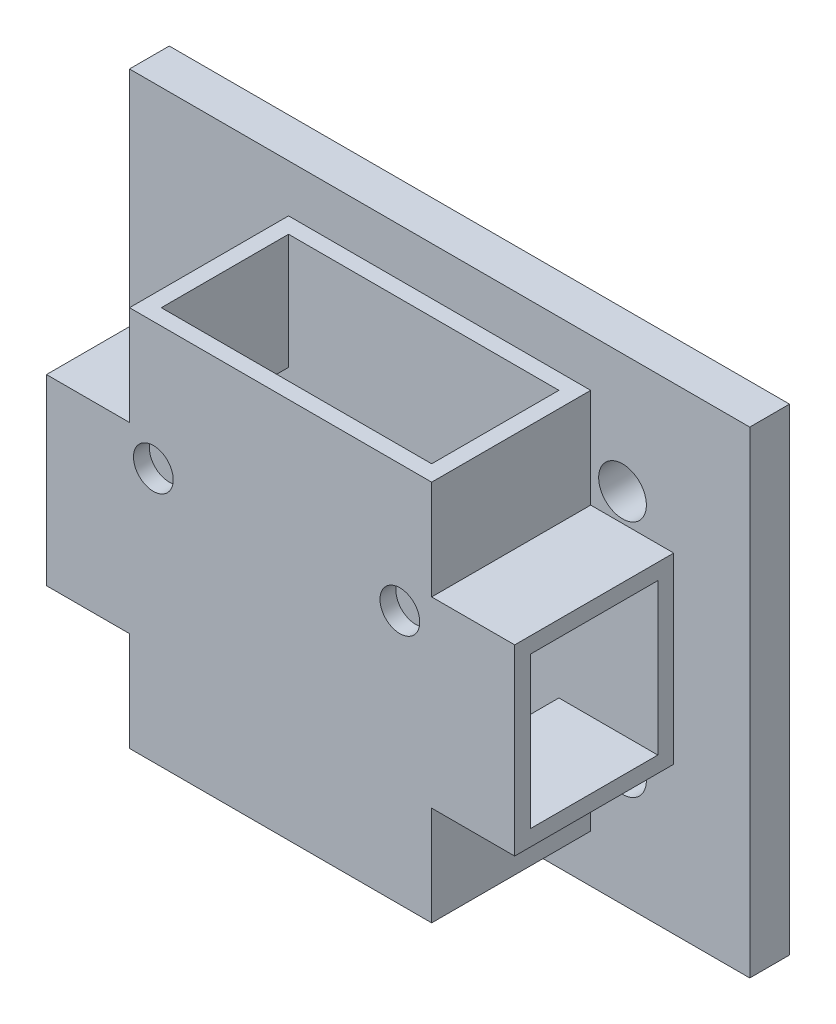
SolidWorks part; units mm, degrees
ref_plane "Front Plane" through (0, 0, 0) normal (0, 0, 1) x (1, 0, 0)
ref_plane "Top Plane" through (0, 0, 0) normal (0, 1, 0) x (1, 0, 0)
ref_plane "Right Plane" through (0, 0, 0) normal (1, 0, 0) x (0, 0, -1)
sketch "Sketch1" plane through (0, 0, 0) normal (0, 0, 1) x (1, 0, 0)
  line L1 (-39.2125, 39.1063) -> (38.7875, 39.1063)
  line L2 (-39.2125, 39.1063) -> (-39.2125, -20.8937)
  line L3 (-39.2125, -20.8937) -> (38.7875, -20.8937)
  line L4 (38.7875, 39.1063) -> (38.7875, -20.8937)
  dimension "D1" = 78
  dimension "D2" = 60
extrude "Boss-Extrude1" add sketch "Sketch1" along normal blind 5
sketch "Sketch7" plane through (0, 0, 5) normal (0, 0, 1) x (1, 0, 0)
  line L0 (-39.2125, 39.1063) -> (-39.2125, -20.8937) construction
  line L1 (-39.2125, -20.8937) -> (38.7875, -20.8937) construction
  line L2 (38.7875, -20.8937) -> (38.7875, 39.1063) construction
  circle A0 centre (-23.2125, 24.1063) radius 3
  circle A1 centre (22.7875, 24.1063) radius 3
  circle A2 centre (22.7875, -5.8937) radius 3
  circle A3 centre (-23.2125, -5.8937) radius 3
  point P0 (-23.2125, 24.1063)
  point P1 (22.7875, 24.1063)
  point P2 (22.7875, -5.8937)
  point P3 (-23.2125, -5.8937)
  dimension "D6" = 6
  dimension "D7" = 6
  dimension "D8" = 6
  dimension "D9" = 6
  dimension "D1" = 46
  dimension "D2" = 46
  dimension "D3" = 30
  dimension "D4" = 16
  dimension "D5" = 15
  dimension "D10" = 30
  dimension "D11" = 16
extrude "Cut-Extrude4" cut sketch "Sketch7" against normal through all
sketch "Sketch8" plane through (0, 0, 5) normal (0, 0, 1) x (1, 0, 0)
  line L0 (-39.2125, 39.1063) -> (-39.2125, -20.8937) construction
  line L1 (-19.2125, 33.1063) -> (18.7875, 33.1063)
  line L2 (-19.2125, 33.1063) -> (-19.2125, -14.8937)
  line L3 (-19.2125, -14.8937) -> (18.7875, -14.8937)
  line L4 (18.7875, 33.1063) -> (18.7875, -14.8937)
  line L5 (-19.2125, 33.1063) -> (18.7875, -14.8937) construction
  line L6 (-19.2125, -14.8937) -> (18.7875, 33.1063) construction
  line L7 (38.7875, -20.8937) -> (38.7875, 39.1063) construction
  line L8 (38.7875, 39.1063) -> (-39.2125, 39.1063) construction
  line L9 (-39.2125, -20.8937) -> (38.7875, -20.8937) construction
  point P0 (-0.2125, 9.1063)
  dimension "D1" = 20
  dimension "D2" = 20
  dimension "D3" = 6
  dimension "D4" = 6
extrude "Boss-Extrude2" add sketch "Sketch8" along normal blind 20
sketch "Sketch9" plane through (0, 0, 5) normal (0, 0, 1) x (1, 0, 0)
  line L0 (38.7875, 39.1063) -> (-39.2125, 39.1063) construction
  line L1 (-29.6518, 20.6063) -> (29.2267, 20.6063)
  line L2 (-29.6518, 20.6063) -> (-29.6518, -2.3937)
  line L3 (-29.6518, -2.3937) -> (29.2267, -2.3937)
  line L4 (29.2267, 20.6063) -> (29.2267, -2.3937)
  line L5 (-29.6518, 20.6063) -> (29.2267, -2.3937) construction
  line L6 (-29.6518, -2.3937) -> (29.2267, 20.6063) construction
  line L7 (-39.2125, -20.8937) -> (38.7875, -20.8937) construction
  point P0 (-0.2125, 9.1063)
  dimension "D1" = 18.5
  dimension "D2" = 18.5
extrude "Boss-Extrude3" add sketch "Sketch9" along normal blind 20
sketch "Sketch10" plane through (-29.6518, 0, 0) normal (-1, 0, 0) x (0, 0, 1)
  line L0 (25, 20.6063) -> (5, 20.6063) construction
  line L1 (7, 18.6063) -> (23, 18.6063)
  line L2 (7, 18.6063) -> (7, -0.3937)
  line L3 (7, -0.3937) -> (23, -0.3937)
  line L4 (23, 18.6063) -> (23, -0.3937)
  line L5 (7, 18.6063) -> (23, -0.3937) construction
  line L6 (7, -0.3937) -> (23, 18.6063) construction
  line L7 (25, -2.3937) -> (5, -2.3937) construction
  line L8 (5, 39.1063) -> (5, -20.8937) construction
  line L9 (25, 20.6063) -> (25, -2.3937) construction
  point P0 (15, 9.1063)
  dimension "D1" = 2
  dimension "D2" = 2
  dimension "D3" = 2
  dimension "D4" = 2
extrude "Cut-Extrude5" cut sketch "Sketch10" against normal blind 60
sketch "Sketch11" plane through (0, -14.8937, 0) normal (0, -1, 0) x (1, 0, 0)
  line L0 (-19.2125, 25) -> (18.7875, 25) construction
  line L1 (-17.2125, 23) -> (16.7875, 23)
  line L2 (-17.2125, 23) -> (-17.2125, 7)
  line L3 (-17.2125, 7) -> (16.7875, 7)
  line L4 (16.7875, 23) -> (16.7875, 7)
  line L5 (-17.2125, 23) -> (16.7875, 7) construction
  line L6 (-17.2125, 7) -> (16.7875, 23) construction
  line L7 (-19.2125, 5) -> (18.7875, 5) construction
  line L8 (-19.2125, 5) -> (-19.2125, 25) construction
  line L9 (18.7875, 25) -> (18.7875, 5) construction
  point P0 (-0.2125, 15)
  dimension "D1" = 2
  dimension "D2" = 2
  dimension "D3" = 2
  dimension "D4" = 2
extrude "Cut-Extrude6" cut sketch "Sketch11" against normal blind 60
sketch "Sketch12" plane through (0, 0, 25) normal (0, 0, 1) x (1, 0, 0)
  line L1 (18.7875, 33.1063) -> (-19.2125, 33.1063) construction
  line L2 (18.7875, 33.1063) -> (-19.2125, 33.1063) construction
  line L5 (29.2267, -2.3937) -> (29.2267, 20.6063) construction
  circle A0 centre (-16.2117, 17.1063) radius 2.5
  circle A1 centre (14.7883, 17.1063) radius 2.5
  dimension "D1" = 5
  dimension "D2" = 5
  dimension "D3" = 31
  dimension "D4" = 14.4385
  dimension "D5" = 16
  dimension "D6" = 16
extrude "Cut-Extrude7" cut sketch "Sketch12" against normal blind 9 contours A1 | A0
